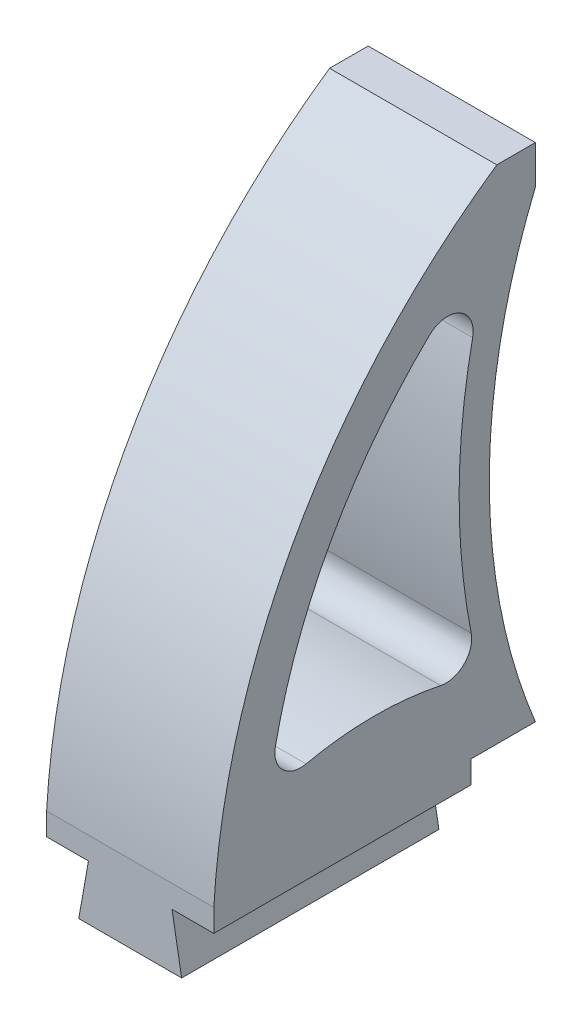
SolidWorks part; units mm, degrees
ref_plane "Front Plane" through (0, 0, 0) normal (0, 0, 1) x (1, 0, 0)
ref_plane "Top Plane" through (0, 0, 0) normal (0, 1, 0) x (1, 0, 0)
ref_plane "Right Plane" through (0, 0, 0) normal (1, 0, 0) x (0, 0, -1)
sketch "Sketch2" plane through (0, 0, 0) normal (1, 0, 0) x (0, 0, -1)
  line L0 (-15.7149, 0) -> (-15.7149, -6)
  line L1 (-15.7149, -6) -> (4.2851, -6)
  line L2 (4.2851, -6) -> (4.2851, 0)
  line L3 (4.2851, 0) -> (9.2851, 0)
  line L4 (6.2851, 39) -> (9.2851, 39)
  line L5 (9.2851, 39) -> (9.2851, 36)
  arc A0 (6.2851, 39) -> (-15.7149, 0) centre (35.1715, -3) ccw
  arc A1 (9.2851, 36) -> (9.2851, 0) centre (52.7017, 18) ccw
  point P11 (0, 0)
  point P12 (0, 0)
  point P13 (0, 0)
  point P14 (52.7017, 18)
  dimension "D1" = 47
  dimension "D2" = 5
  dimension "D3" = 6
  dimension "D4" = 20
  dimension "D5" = 3
  dimension "D6" = 3
  dimension "D7" = 39
  dimension "D8" = 25
extrude "Boss-Extrude2" add sketch "Sketch2" along normal mid plane 13
sketch "Sketch3" plane through (0, 0, 15.7149) normal (0, 0, 1) x (1, 0, 0)
  line L0 (0, -6) -> (0, 25.2926) construction
  line L1 (6.5, -6) -> (-6.5, -6) construction
  line L2 (6.5, -1.7465) -> (3.25, -1.7465)
  line L3 (6.5, 0) -> (6.5, -6) construction
  line L4 (3.25, -1.7465) -> (4, -6)
  line L5 (-3.25, -1.7465) -> (-4, -6)
  line L6 (-6.5, -1.7465) -> (-3.25, -1.7465)
  line M4 (-6.5, 0) -> (-6.5, -6)
  line M5 (-6.5, -6) -> (6.5, -6)
  line M6 (6.5, -6) -> (6.5, 0)
  dimension "D1" = 6.5
  dimension "D2" = 8
  dimension "D3" = 80
extrude "Cut-Extrude1" cut sketch "Sketch3" against normal through all contours L2 L4 M5 M6 | L6 L5 M4 M5
sketch "Sketch4" plane through (6.5, 0, 0) normal (1, 0, 0) x (0, 0, -1)
  line L0 (9.2851, 0) -> (-15.7149, 0) construction
  line L1 (-3.2149, 0) -> (-3.2149, 33.0932) construction
  line L2 (4.2851, -1.7465) -> (-15.7149, -1.7465) construction
  arc A0 (6.2851, 39) -> (-15.7149, 0) centre (35.1715, -3) ccw construction
  arc A1 (-8.5451, 6.0791) -> (1.9204, 6.1208) centre (-3.2149, -18.3461) cw
  arc A2 (4.2937, 8.4638) -> (4.4066, 28.3029) centre (53.3554, 18.1045) cw
  arc A3 (1.0614, 30.1516) -> (-10.9297, 8.44) centre (30.192, -0.1041) ccw
  arc A4 (-8.5451, 6.0791) -> (-10.9297, 8.44) centre (-8.9716, 8.0331) cw
  arc A5 (1.9204, 6.1208) -> (4.2937, 8.4638) centre (2.3312, 8.0782) ccw
  arc A6 (4.4066, 28.3029) -> (1.0614, 30.1516) centre (2.4486, 28.7108) ccw
  point P19 (-11.4649, 5.2535)
  point P22 (5.0351, 5.2535)
  point P25 (6.0351, 34.2535)
  dimension "D3" = 50
  dimension "D4" = 25
  dimension "D5" = 42
  dimension "D8" = 2
  dimension "D1" = 16.5
  dimension "D2" = 7
  dimension "D6" = 29
  dimension "D7" = 17.5
extrude "Cut-Extrude2" cut sketch "Sketch4" against normal through all contours A2 A6 A3 A4 A1 A5
